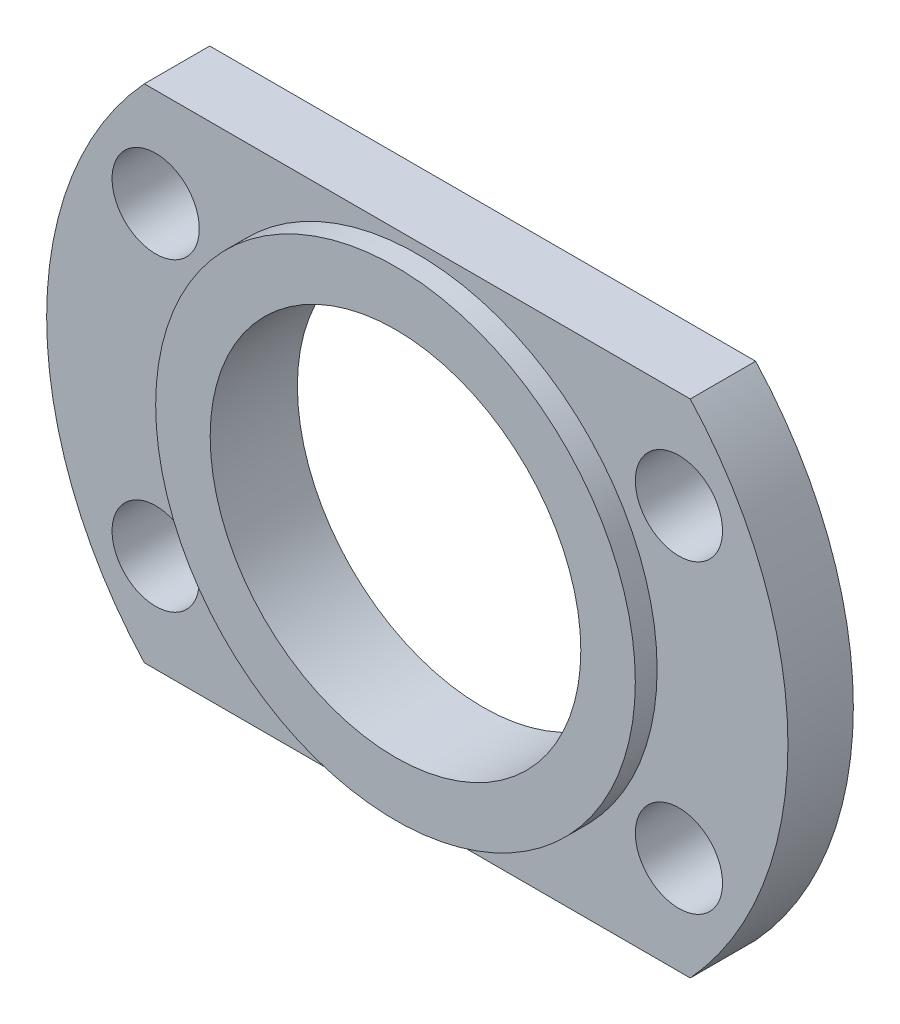
SolidWorks part; units mm, degrees
ref_plane "前视基准面" through (0, 0, 0) normal (0, 0, 1) x (1, 0, 0)
ref_plane "上视基准面" through (0, 0, 0) normal (0, 1, 0) x (1, 0, 0)
ref_plane "右视基准面" through (0, 0, 0) normal (1, 0, 0) x (0, 0, -1)
sketch "草图1" plane through (0, 0, 0) normal (0, 0, 1) x (1, 0, 0)
  line L0 (-20.3951, 0) -> (20.3154, 0) construction
  line L1 (-12.52, -11.5) -> (12.52, -11.5)
  line L2 (-12.52, 11.5) -> (12.52, 11.5)
  line L3 (-20.3951, -11.5) -> (20.3154, -11.5) construction
  line L4 (-20.3951, 11.5) -> (20.3154, 11.5) construction
  line L5 (0, -14.1138) -> (0, 0) construction
  arc A0 (12.52, -11.5) -> (12.52, 11.5) centre (0, 0) ccw
  arc A1 (-12.52, 11.5) -> (-12.52, -11.5) centre (0, 0) ccw
  circle A2 centre (-12, -7) radius 2
  circle A3 centre (-12, 7) radius 2
  circle A4 centre (12, 7) radius 2
  circle A5 centre (12, -7) radius 2
  circle A6 centre (0, 0) radius 8.5
  dimension "D1" = 34
  dimension "D4" = 4
  dimension "D5" = 24
  dimension "D7" = 17
  dimension "D6" = 14
  dimension "D2" = 11.5
  dimension "D3" = 11.5
extrude "凸台-拉伸1" add sketch "草图1" along normal blind 3
sketch "草图2" plane through (0, 0, 3) normal (0, 0, 1) x (1, 0, 0)
  circle A0 centre (0, 0) radius 11
  circle A1 centre (0, 0) radius 8.5 construction
  circle A2 centre (0, 0) radius 8.5
  dimension "D1" = 22
extrude "凸台-拉伸2" add sketch "草图2" along normal blind 1
